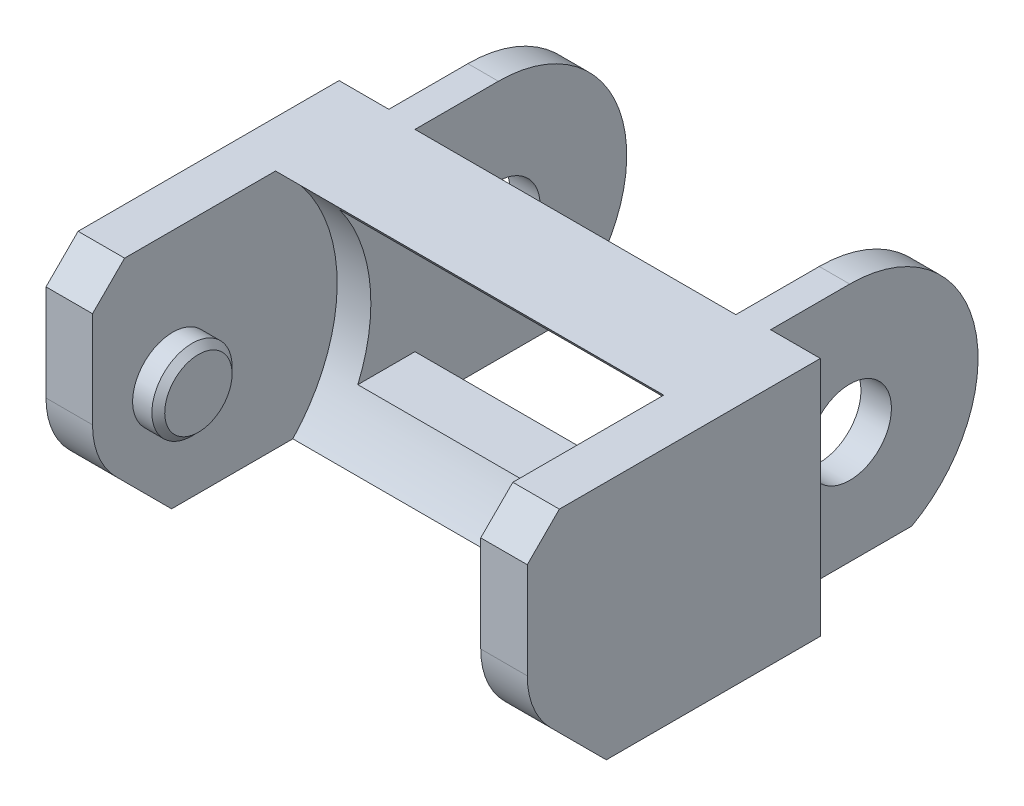
SolidWorks part; units mm, degrees
ref_plane "前基準面" through (0, 0, 0) normal (0, 0, 1) x (1, 0, 0)
ref_plane "上基準面" through (0, 0, 0) normal (0, 1, 0) x (1, 0, 0)
ref_plane "右基準面" through (0, 0, 0) normal (1, 0, 0) x (0, 0, -1)
sketch "草圖1" plane through (0, 0, 0) normal (0, 0, 1) x (1, 0, 0)
  line L1 (-12.751, 5.0503) -> (17.249, 5.0503)
  line L2 (-12.751, 5.0503) -> (-12.751, -9.9497)
  line L3 (-12.751, -9.9497) -> (17.249, -9.9497)
  line L4 (17.249, 5.0503) -> (17.249, -9.9497)
  dimension "D1" = 30
  dimension "D2" = 15
extrude "填料-伸長1" add sketch "草圖1" along normal blind 18
sketch "草圖2" plane through (0, 0, 18) normal (0, 0, 1) x (1, 0, 0)
  line L0 (-12.751, 5.0503) -> (-12.751, -9.9497) construction
  line L1 (-7.751, 3.0503) -> (12.249, 3.0503)
  line L2 (-7.751, 3.0503) -> (-7.751, -6.9497)
  line L3 (-7.751, -6.9497) -> (12.249, -6.9497)
  line L4 (12.249, 3.0503) -> (12.249, -6.9497)
  line L5 (17.249, -9.9497) -> (17.249, 5.0503) construction
  line L6 (17.249, 5.0503) -> (-12.751, 5.0503) construction
  line L7 (-12.751, -9.9497) -> (17.249, -9.9497) construction
  dimension "D1" = 5
  dimension "D2" = 5
  dimension "D3" = 2
  dimension "D4" = 3
extrude "除料-伸長1" cut sketch "草圖2" against normal up to next
sketch "草圖3" plane through (0, -6.9497, 0) normal (0, 1, 0) x (1, 0, 0)
  line L0 (-7.751, 0) -> (-7.751, -18) construction
  line L1 (-7.751, -6) -> (12.249, -6)
  line L2 (-7.751, -6) -> (-7.751, -18)
  line L3 (-7.751, -18) -> (12.249, -18)
  line L4 (12.249, -6) -> (12.249, -18)
  dimension "D1" = 12
extrude "除料-伸長2" cut sketch "草圖3" against normal up to next
sketch "草圖4" plane through (-7.751, 0, 0) normal (1, 0, 0) x (0, 0, -1)
  line L0 (-18, 3.0503) -> (-18, -9.9497) construction
  line L1 (-18, -9.9497) -> (-6, -9.9497) construction
  line L3 (-13, -2.9497) -> (-18, -2.9497)
  line L4 (-13, -2.9497) -> (-13, 7.8945)
  line L5 (-18, -2.9497) -> (-18, 7.8945)
  line L6 (-13, 7.8945) -> (-18, 7.8945)
  circle A0 centre (-13, -2.9497) radius 10.25
  line M3 (0, 3.0503) -> (-18, 3.0503)
  line M4 (-18, 3.0503) -> (-18, -9.9497)
  line M5 (-18, -9.9497) -> (-6, -9.9497)
  line M6 (-6, -9.9497) -> (-6, -6.9497)
  line M7 (-6, -6.9497) -> (0, -6.9497)
  dimension "D2" = 7
  dimension "D3" = 20.5
  dimension "D1" = 5
extrude "除料-伸長5" cut sketch "草圖4" against normal blind 2.1 and the other way blind 22.1 contours L3 L4 M3 M4 | A0 L4 L3 M7 M3 M4 M5 M6 | A0 L4 L6 L5 | A0 L4 M3 | L4 A0 L5 M3 | L5 A0 M7 M6 M5 M4
sketch "草圖5" plane through (14.349, 0, 0) normal (-1, 0, 0) x (0, 0, 1)
  circle A0 centre (13, -2.9497) radius 2.5
  arc A2 (6.592, 5.0503) -> (5.5125, -9.9497) centre (13, -2.9497) ccw construction
  dimension "D1" = 5
extrude "填料-伸長2" add sketch "草圖5" along normal blind 1.6
sketch "草圖6" plane through (-9.851, 0, 0) normal (1, 0, 0) x (0, 0, -1)
  circle A0 centre (-13, -2.9497) radius 2.5
  arc A1 (-5.5125, -9.9497) -> (-6.592, 5.0503) centre (-13, -2.9497) ccw construction
  dimension "D1" = 5
extrude "填料-伸長3" add sketch "草圖6" along normal blind 1.6
chamfer "導角1" distance 0.4 angle 45 2 edges at (-8.251, -0.4497, 13) (12.749, -5.4497, 13)
sketch "草圖7" plane through (-9.851, 0, 0) normal (1, 0, 0) x (0, 0, -1)
  line L0 (-13.0711, -9.9497) -> (-18, -5.0208)
  line L1 (-18, -9.9497) -> (-5.5125, -9.9497) construction
  line L2 (-18, -9.9497) -> (-18, 5.0503) construction
  circle A0 centre (-13, -2.9497) radius 2.5 construction
  line M4 (-18, 5.0503) -> (-18, -9.9497)
  line M5 (-18, -9.9497) -> (-5.5125, -9.9497)
  dimension "D1" = 45
  dimension "D2" = 5
extrude "除料-伸長6" cut sketch "草圖7" against normal through all both and the other way through all contours L0 M5 M4
sketch "草圖8" plane through (-9.851, 0, 0) normal (1, 0, 0) x (0, 0, -1)
  line L0 (-18, -5.0208) -> (-18, -2.9497)
  line L1 (-18, -5.0208) -> (-15.5355, -7.4853)
  line L2 (-13.0711, -9.9497) -> (-18, -5.0208) construction
  circle A0 centre (-13, -2.9497) radius 5
  line M1 (-18, -5.0208) -> (-13.0711, -9.9497)
  line M5 (-18, 5.0503) -> (-18, -5.0208)
extrude "除料-伸長7" cut sketch "草圖8" against normal through all both and the other way through all contours A0 M5 M1
sketch "草圖9" plane through (0, 0, 0) normal (0, 0, -1) x (-1, 0, 0)
  line L0 (-17.249, 5.0503) -> (12.751, 5.0503) construction
  line L1 (-12.249, 5.0503) -> (7.751, 5.0503)
  line L2 (-12.249, 5.0503) -> (-12.249, -9.9497)
  line L3 (-12.249, -9.9497) -> (7.751, -9.9497)
  line L4 (7.751, 5.0503) -> (7.751, -9.9497)
  line L5 (12.751, -9.9497) -> (-17.249, -9.9497) construction
  line L6 (-12.249, 3.0503) -> (-12.249, -6.9497) construction
  line L7 (9.651, -9.9497) -> (-14.149, -9.9497)
  line L8 (9.651, -9.9497) -> (9.651, 5.0503)
  line L9 (9.651, 5.0503) -> (-14.149, 5.0503)
  line L10 (-14.149, -9.9497) -> (-14.149, 5.0503)
  line L11 (7.751, -6.9497) -> (7.751, 3.0503) construction
  line M6 (7.751, 3.0503) -> (7.751, -6.9497)
  line M8 (-12.249, -6.9497) -> (-12.249, 3.0503)
  line M10 (12.751, 5.0503) -> (-17.249, 5.0503)
  line M12 (-17.249, -9.9497) -> (12.751, -9.9497)
  dimension "D1" = 1.9
  dimension "D2" = 1.9
extrude "填料-伸長4" add sketch "草圖9" along normal blind 20 contours L8 L4 M12 M10 M6 | L10 L2 M12 M8 M10
sketch "草圖10" plane through (14.149, 0, 0) normal (1, 0, 0) x (0, 0, -1)
  line L0 (0, -9.9497) -> (0, 5.0503) construction
  line L1 (20, -9.9497) -> (0, -9.9497) construction
  circle A0 centre (5.2, -2.9497) radius 2.6
  dimension "D1" = 5.2
  dimension "D2" = 5.2
  dimension "D3" = 7
extrude "除料-伸長8" cut sketch "草圖10" against normal through all
sketch "草圖12" plane through (14.149, 0, 0) normal (1, 0, 0) x (0, 0, -1)
  line L1 (5.2, 5.0503) -> (18.304, 5.0503)
  line L2 (5.2, 5.0503) -> (5.2, -15.4926)
  line L3 (5.2, -15.4926) -> (18.304, -15.4926)
  line L4 (18.304, 5.0503) -> (18.304, -15.4926)
  circle A0 centre (5.2, -2.9497) radius 8
  line M3 (0, -9.9497) -> (20, -9.9497)
  line M4 (20, -9.9497) -> (20, 5.0503)
  line M5 (20, 5.0503) -> (0, 5.0503)
extrude "除料-伸長9" cut sketch "草圖12" against normal through all both and the other way through all contours A0 L4 M3 M5 | L4 M5 M3 M4
chamfer "導角2" distance 2 angle 45 2 edges at (15.799, 5.0503, 18) (-11.301, 5.0503, 18)
sketch "草圖17" plane through (0, 0, 0) normal (0, 0, -1) x (-1, 0, 0)
  line L1 (-17.249, 5.0503) -> (-14.149, 5.0503)
  line L2 (-17.249, 5.0503) -> (-17.249, -9.9497)
  line L3 (-17.249, -9.9497) -> (-14.149, -9.9497)
  line L4 (-14.149, 5.0503) -> (-14.149, -9.9497)
  line L5 (9.651, 5.0503) -> (12.751, 5.0503)
  line L6 (9.651, 5.0503) -> (9.651, -9.9497)
  line L7 (9.651, -9.9497) -> (12.751, -9.9497)
  line L8 (12.751, 5.0503) -> (12.751, -9.9497)
extrude "填料-伸長8" add sketch "草圖17" along normal blind 0.27
